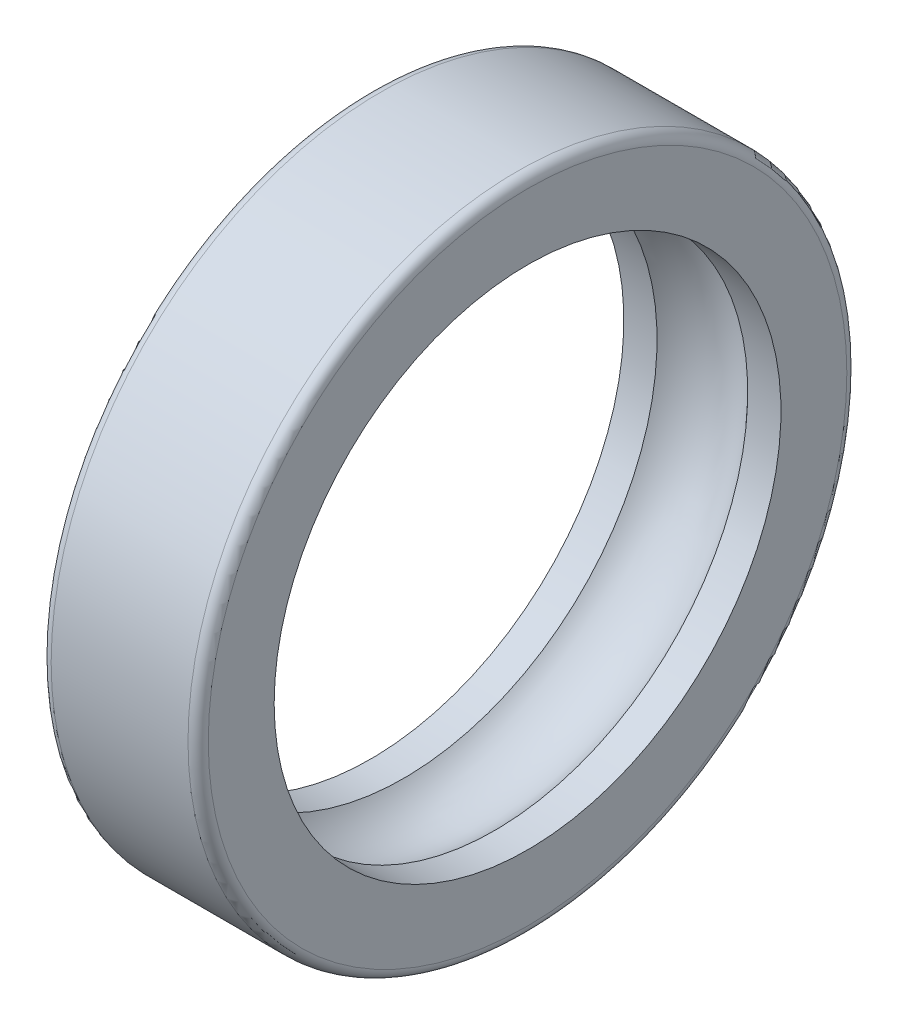
SolidWorks part; units mm, degrees
ref_plane "Front Plane" through (0, 0, 0) normal (0, 0, 1) x (1, 0, 0)
ref_plane "Top Plane" through (0, 0, 0) normal (0, 1, 0) x (1, 0, 0)
ref_plane "Right Plane" through (0, 0, 0) normal (1, 0, 0) x (0, 0, -1)
sketch "Sketch1" plane through (0, 0, 0) normal (0, 0, 1) x (1, 0, 0)
  line L0 (0, 0) -> (39606.4451, 0) construction
  line L1 (0, 0) -> (0, -39606.4451) construction
  line L2 (-13.5, 65) -> (13.5, 65)
  line L3 (-15.5, 63) -> (-15.5, 50)
  line L4 (-15.5, 50) -> (-8.9443, 50)
  line L5 (8.9443, 50) -> (15.5, 50)
  line L6 (15.5, 50) -> (15.5, 63)
  arc A1 (13.5, 65) -> (15.5, 63) centre (13.5, 63) cw
  arc A2 (-13.5, 65) -> (-15.5, 63) centre (-13.5, 63) ccw
  arc A3 (-8.9443, 50) -> (8.9443, 50) centre (0, 42) cw
  point P7 (0, 65)
  point P8 (0, 0)
  point P10 (0, 0)
  point P12 (0, 0)
  point P17 (15.5, 65)
  point P20 (-15.5, 65)
  dimension "D5" = 2
  dimension "D6" = 12
  dimension "D1" = 31
  dimension "D2" = 130
  dimension "D3" = 100
  dimension "D4" = 8
revolve "Revolve1" add sketch "Sketch1" angle 360 about L0
